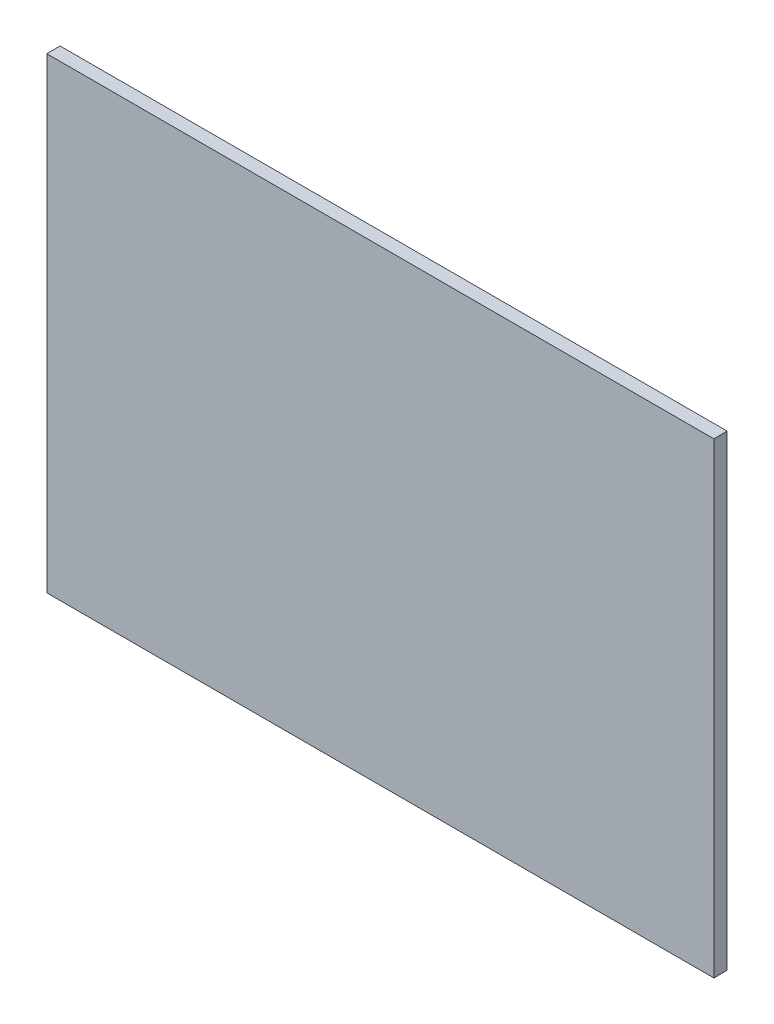
SolidWorks part; units mm, degrees
ref_plane "Front Plane" through (0, 0, 0) normal (0, 0, 1) x (1, 0, 0)
ref_plane "Top Plane" through (0, 0, 0) normal (0, 1, 0) x (1, 0, 0)
ref_plane "Right Plane" through (0, 0, 0) normal (1, 0, 0) x (0, 0, -1)
sketch "Sketch1" plane through (0, 0, 0) normal (0, 0, 1) x (1, 0, 0)
  line L0 (-471.3357, 29.3863) -> (-471.3357, -670.6137)
  line L1 (-471.3357, -670.6137) -> (528.6643, -670.6137)
  line L2 (528.6643, -670.6137) -> (528.6643, 29.3863)
  line L3 (528.6643, 29.3863) -> (-471.3357, 29.3863)
  dimension "D1" = 1000
  dimension "D2" = 700
extrude "Boss-Extrude1" add sketch "Sketch1" along normal blind 20
